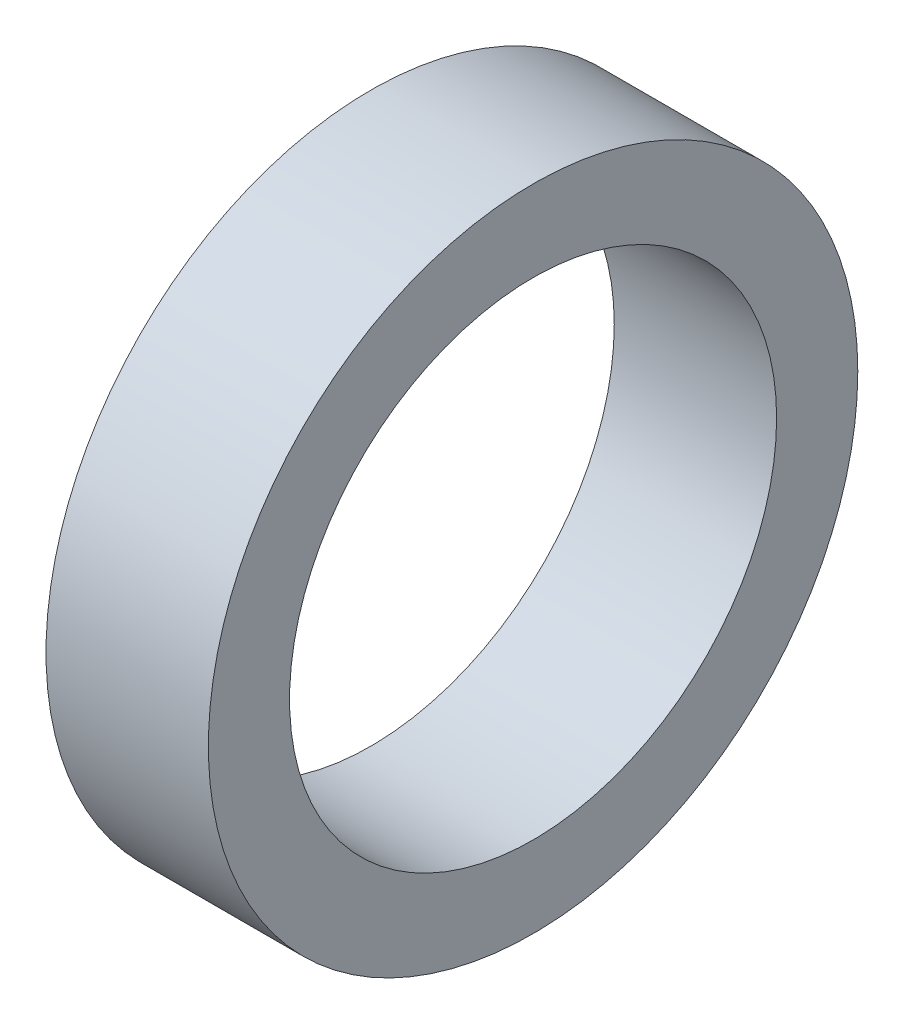
SolidWorks part; units mm, degrees
material "POM Acetal Copolymer"
ref_plane "Front Plane" through (0, 0, 0) normal (0, 0, 1) x (1, 0, 0)
ref_plane "Top Plane" through (0, 0, 0) normal (0, 1, 0) x (1, 0, 0)
ref_plane "Right Plane" through (0, 0, 0) normal (1, 0, 0) x (0, 0, -1)
sketch "Sketch1" plane through (0, 0, 0) normal (1, 0, 0) x (0, 0, -1)
  circle A0 centre (0, 0) radius 2.3813
  circle A1 centre (0, 0) radius 3.175
  dimension "D1" = 4.7625
  dimension "D2" = 6.35
extrude "Boss-Extrude1" add sketch "Sketch1" along normal blind 1.5875
